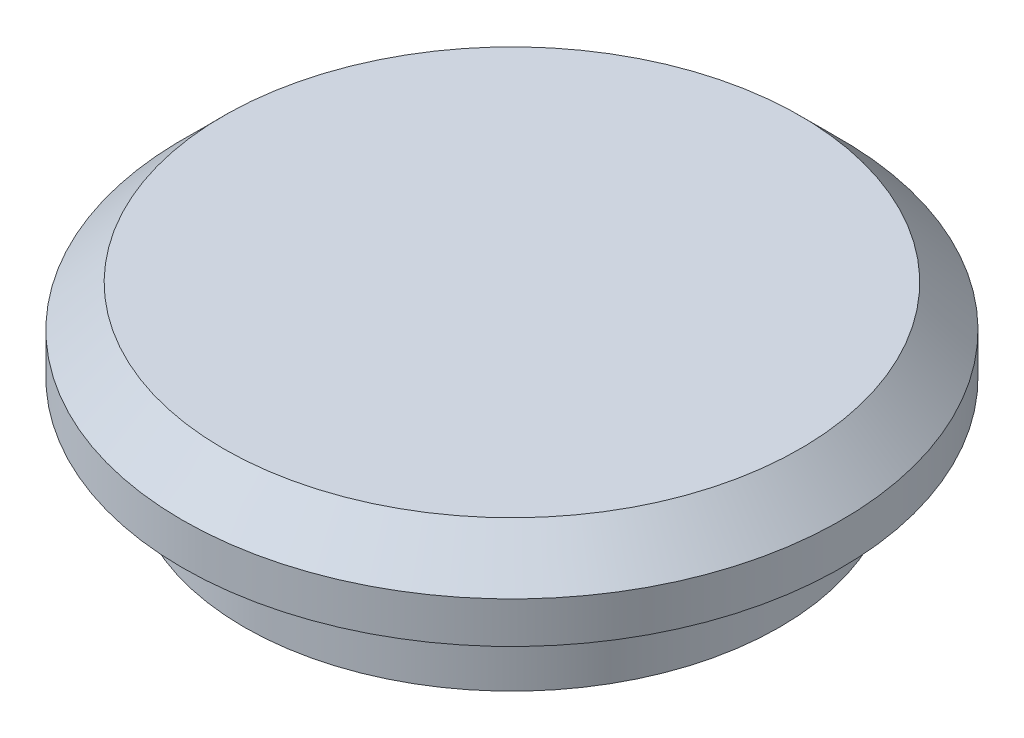
SolidWorks part; units mm, degrees
material "AISI 304"
ref_plane "Front Plane" through (0, 0, 0) normal (0, 0, 1) x (1, 0, 0)
ref_plane "Top Plane" through (0, 0, 0) normal (0, 1, 0) x (1, 0, 0)
ref_plane "Right Plane" through (0, 0, 0) normal (1, 0, 0) x (0, 0, -1)
sketch "Sketch1" plane through (0, 0, 0) normal (0, 1, 0) x (1, 0, 0)
  circle A0 centre (0, 0) radius 6.5
  dimension "D1" = 13
extrude "Boss-Extrude1" add sketch "Sketch1" along normal blind 4
sketch "Sketch2" plane through (0, 4, 0) normal (0, 1, 0) x (1, 0, 0)
  circle A0 centre (0, 0) radius 8
  dimension "D1" = 16
extrude "Boss-Extrude2" add sketch "Sketch2" against normal blind 2
chamfer "Chamfer1" distance 1 angle 45 1 edges at (0, 4, 8)
